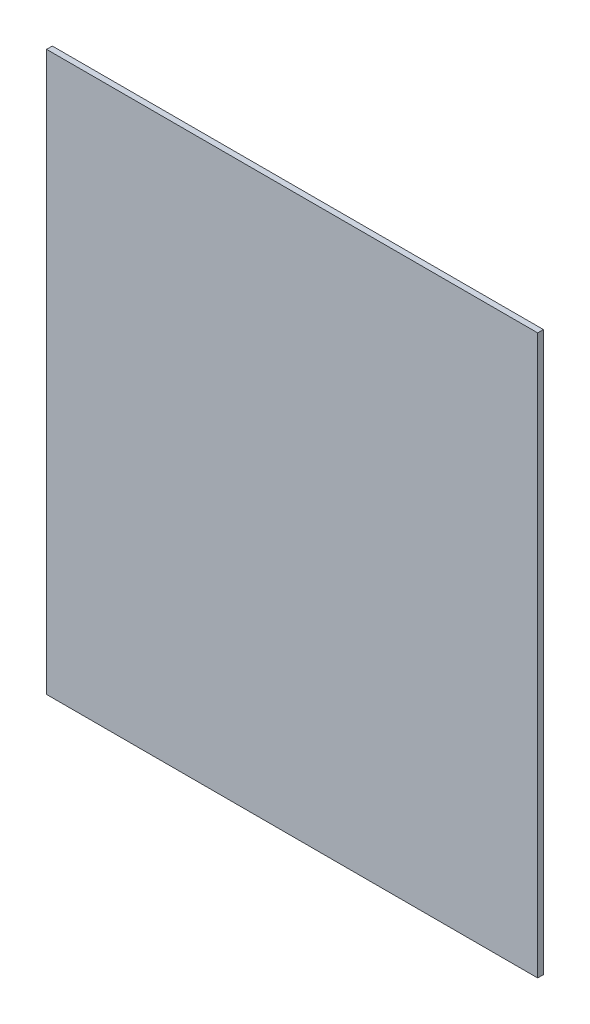
SolidWorks part; units mm, degrees
ref_plane "Alzado" through (0, 0, 0) normal (0, 0, 1) x (1, 0, 0)
ref_plane "Planta" through (0, 0, 0) normal (0, 1, 0) x (1, 0, 0)
ref_plane "Vista lateral" through (0, 0, 0) normal (1, 0, 0) x (0, 0, -1)
sketch "Croquis1" plane through (0, 0, 0) normal (0, 0, 1) x (1, 0, 0)
  line L1 (-163.5483, 193.1712) -> (92.3517, 193.1712)
  line L2 (-163.5483, 193.1712) -> (-163.5483, -97.9288)
  line L3 (-163.5483, -97.9288) -> (92.3517, -97.9288)
  line L4 (92.3517, 193.1712) -> (92.3517, -97.9288)
  line L5 (-163.5483, 193.1712) -> (92.3517, -97.9288) construction
  line L6 (-163.5483, -97.9288) -> (92.3517, 193.1712) construction
  point P0 (-35.5983, 47.6212)
  dimension "D1" = 291.1
  dimension "D2" = 255.9
extrude "Saliente-Extruir1" add sketch "Croquis1" along normal blind 3
